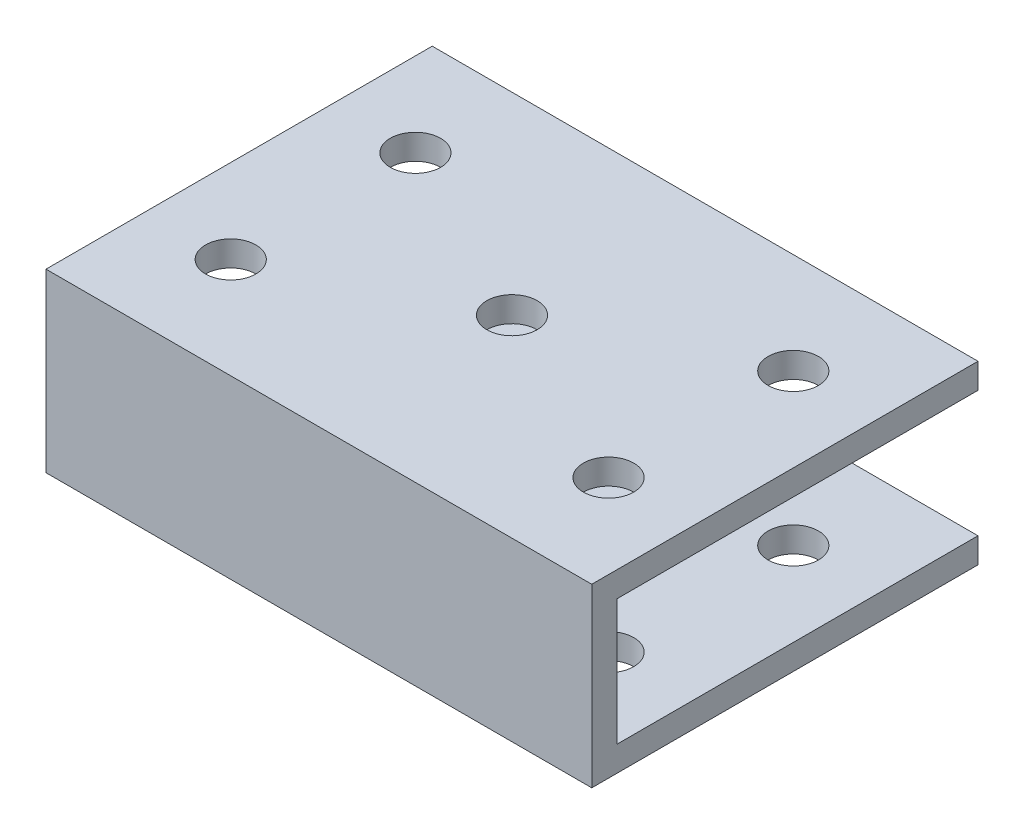
SolidWorks part; units mm, degrees
ref_plane "前视" through (0, 0, 0) normal (0, 0, 1) x (1, 0, 0)
ref_plane "上视" through (0, 0, 0) normal (0, 1, 0) x (1, 0, 0)
ref_plane "右视" through (0, 0, 0) normal (1, 0, 0) x (0, 0, -1)
sketch "草图1" plane through (0, 0, 0) normal (0, 1, 0) x (1, 0, 0)
  line L1 (0, 0) -> (65, 0)
  line L2 (0, 0) -> (0, 46)
  line L3 (0, 46) -> (65, 46)
  line L4 (65, 0) -> (65, 46)
  dimension "D1" = 65
  dimension "D2" = 46
extrude "凸台-拉伸1" add sketch "草图1" along normal blind 3
sketch "草图2" plane through (0, 0, 0) normal (0, 0, 1) x (1, 0, 0)
  line L1 (0, 3) -> (65, 3)
  line L2 (0, 3) -> (0, 18)
  line L3 (0, 18) -> (65, 18)
  line L4 (65, 3) -> (65, 18)
  dimension "D1" = 15
extrude "凸台-拉伸2" add sketch "草图2" against normal blind 3
sketch "草图3" plane through (0, 18, 0) normal (0, 1, 0) x (1, 0, 0)
  line L1 (0, 0) -> (65, 0)
  line L2 (0, 0) -> (0, 46)
  line L3 (0, 46) -> (65, 46)
  line L4 (65, 0) -> (65, 46)
  dimension "D1" = 46
extrude "凸台-拉伸3" add sketch "草图3" along normal blind 3
sketch "草图4" plane through (0, 0, 0) normal (0, -1, 0) x (1, 0, 0)
  line L0 (0, -23) -> (65, -23) construction
  line L1 (0, -46) -> (0, 0) construction
  line L2 (65, 0) -> (65, -46) construction
  line L3 (32.5, -46) -> (32.5, 0) construction
  line L4 (65, -46) -> (0, -46) construction
  line L5 (0, 0) -> (65, 0) construction
  circle A0 centre (32.5, -23) radius 3
  circle A1 centre (55, -34) radius 3
  circle A2 centre (55, -12) radius 3
  circle A3 centre (10, -34) radius 3
  circle A4 centre (10, -12) radius 3
  dimension "D1" = 6
  dimension "D2" = 6
  dimension "D3" = 22
  dimension "D4" = 45
extrude "切除-拉伸1" cut sketch "草图4" against normal through all
